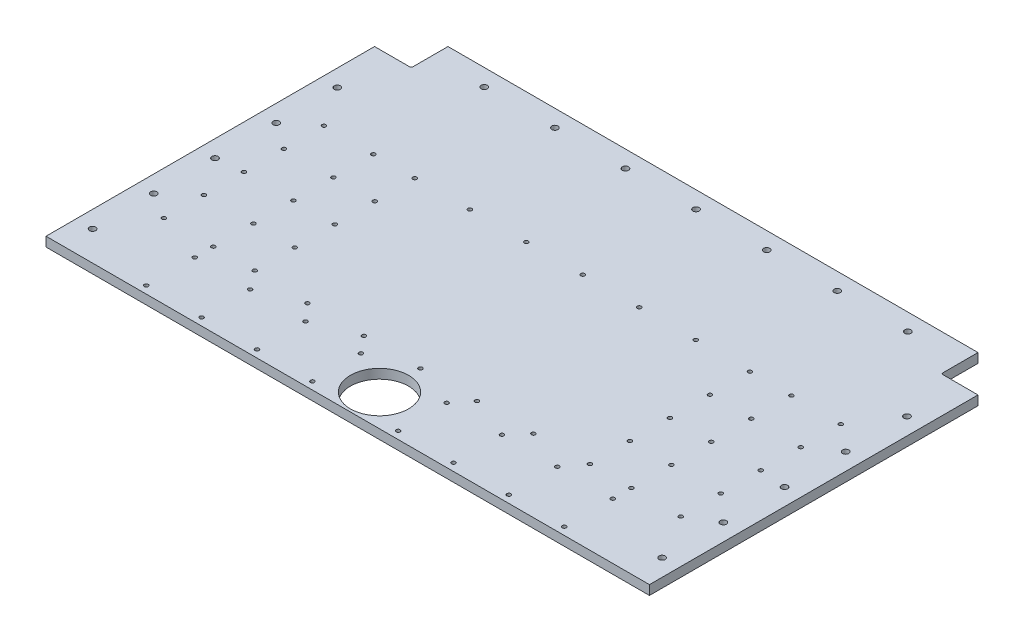
SolidWorks part; units mm, degrees
material "3.1355 (EN-AW 2024)"
ref_plane "Спереди" through (0, 0, 0) normal (0, 0, 1) x (1, 0, 0)
ref_plane "Сверху" through (0, 0, 0) normal (0, 1, 0) x (1, 0, 0)
ref_plane "Справа" through (0, 0, 0) normal (1, 0, 0) x (0, 0, -1)
sketch "Эскиз1" plane through (0, 0, 0) normal (0, 1, 0) x (1, 0, 0)
  line L1 (-320.5, 194) -> (320.5, 194)
  line L2 (-320.5, 194) -> (-320.5, -194)
  line L3 (-320.5, -194) -> (320.5, -194)
  line L4 (320.5, 194) -> (320.5, -194)
  line L5 (-320.5, 194) -> (320.5, -194) construction
  line L6 (-320.5, -194) -> (320.5, 194) construction
  point P0 (0, 0)
  dimension "D1" = 641
  dimension "D2" = 388
extrude "База" add sketch "Эскиз1" along normal blind 10
hole_wizard "Винты M6" positions "Эскиз2" profile "Эскиз3" countersink size "M6" standard "DIN" end condition through all
sketch "Эскиз2" plane through (0, 0, 0) normal (0, -1, 0) x (-1, 0, 0)
  line L2 (-302.5, -97.5) -> (-302.5, -32.5) construction
  line L3 (-302.5, -32.5) -> (-302.5, 32.5) construction
  line L4 (-302.5, 32.5) -> (-302.5, 97.5) construction
  line L7 (-320.5, -194) -> (-320.5, 194) construction
  line L8 (0, 176) -> (-75, 176) construction
  line L9 (-75, 176) -> (-150, 176) construction
  line L10 (-150, 176) -> (-225, 176) construction
  line L15 (-320.5, 194) -> (320.5, 194) construction
  line L16 (-302.5, -162.5) -> (-302.5, -97.5) construction
  point P4 (-302.5, -97.5)
  point P6 (-302.5, -32.5)
  point P8 (-302.5, 32.5)
  point P12 (-302.5, 97.5)
  point P36 (0, 176)
  point P38 (-75, 176)
  point P40 (-150, 176)
  point P42 (-225, 176)
  point P67 (-302.5, 0)
  point P68 (-302.5, -162.5)
  dimension "D1" = 65
  dimension "D2" = 18
  dimension "D3" = 18
  dimension "D4" = 75
sketch "Эскиз3" plane through (302.5, 0, 97.5) normal (1, 0, 0) x (0, 0, -1)
  line L0 (0, 0) -> (0, 10)
  line L1 (0, 10) -> (3.3, 10)
  line L2 (3.3, 10) -> (3.3, 3)
  line L3 (3.3, 3) -> (6.3, 0)
  line L5 (6.3, 0) -> (0, 0)
  line L6 (-3.3, 3) -> (-6.3, 0) construction
  line L11 (0, -6.35) -> (0, 107.95) construction
  dimension "Диаметр сквозного отверстия" = 6.6
  dimension "Глубина сквозного отверстия" = 10
  dimension "Диаметр передней зенковки" = 12.6
  dimension "Угол передней зенковки" = 90
mirror "Зеркальное отражение1" about plane through (0, 0, 0) normal (1, 0, 0) of "Винты M6"
sketch "Эскиз4" plane through (0, 0, 0) normal (0, -1, 0) x (1, 0, 0)
  line L1 (-320.5, -194) -> (-281.5, -194)
  line L2 (-320.5, -194) -> (-320.5, -155)
  line L3 (-320.5, -155) -> (-281.5, -155)
  line L4 (-281.5, -194) -> (-281.5, -155)
  line L5 (320.5, -194) -> (281.5, -194)
  line L6 (320.5, -194) -> (320.5, -155)
  line L7 (320.5, -155) -> (281.5, -155)
  line L8 (281.5, -194) -> (281.5, -155)
  dimension "D1" = 39
extrude "ВырезПрофиля" cut sketch "Эскиз4" against normal through all
fillet "Скругление1" radius 1.5 2 edges at (281.5, 5, -155) (-281.5, 5, -155)
sketch "РазмерСтола" plane through (0, 10, 0) normal (0, 1, 0) x (1, 0, 0)
  line L0 (281.5, 194) -> (-281.5, 194) construction
  line L1 (-130, 49.7) -> (130, 49.7) construction
  line L2 (-130, 49.7) -> (-130, -100.3) construction
  line L3 (-130, -100.3) -> (130, -100.3) construction
  line L4 (130, 49.7) -> (130, -100.3) construction
  point P6 (0, 49.7)
  dimension "D1" = 144.3
  dimension "D2" = 260
  dimension "D3" = 150
sketch "ДополнительныеЗоны" plane through (0, 10, 0) normal (0, 1, 0) x (1, 0, 0)
  line L0 (-320.5, -194) -> (320.5, -194) construction
  line L3 (-170, 66.5) -> (170, 66.5) construction
  line L5 (-170, 66.5) -> (-230, 66.5) construction
  line L7 (-170, -126.5) -> (-230, -126.5) construction
  line L8 (-230, 66.5) -> (-230, -126.5) construction
  line L9 (170, 66.5) -> (230, 66.5) construction
  line L11 (170, -126.5) -> (230, -126.5) construction
  line L12 (230, 66.5) -> (230, -126.5) construction
  line L13 (-230, -126.5) -> (-37.5, -126.5) construction
  line L14 (-230, -126.5) -> (-230, -194) construction
  line L15 (-230, -194) -> (-37.5, -194) construction
  line L16 (-37.5, -126.5) -> (-37.5, -194) construction
  line L18 (230, -126.5) -> (37.5, -126.5) construction
  line L19 (230, -126.5) -> (230, -194) construction
  line L20 (230, -194) -> (37.5, -194) construction
  line L21 (37.5, -126.5) -> (37.5, -194) construction
  line L23 (-170, 66.5) -> (-170, -126.5) construction
  line L24 (-170, -126.5) -> (170, -126.5) construction
  line L25 (170, 66.5) -> (170, -126.5) construction
  point P0 (0, 66.5)
  dimension "D1" = 60
  dimension "D2" = 75
  dimension "D3" = 67.5
  dimension "D4" = 193
  dimension "D5" = 460
hole_wizard "M5" positions "Эскиз6" profile "Эскиз7" tap size "M5" standard "DIN" end condition through all
sketch "Эскиз6" plane through (0, 0, 0) normal (0, -1, 0) x (-1, 0, 0)
  line L12 (130, -100.3) -> (-130, -100.3) construction
  line L13 (130, 49.7) -> (-130, 49.7) construction
  line L14 (120, 55.7) -> (60, 55.7) construction
  line L15 (60, 55.7) -> (0, 55.7) construction
  line L16 (0, 55.7) -> (-60, 55.7) construction
  line L17 (-60, 55.7) -> (-120, 55.7) construction
  line L18 (274.5, -114.75) -> (274.5, -72.25) construction
  line L19 (274.5, -72.25) -> (274.5, -29.75) construction
  line L20 (274.5, -29.75) -> (274.5, 12.75) construction
  line L21 (274.5, 12.75) -> (274.5, 55.25) construction
  line L22 (222, 55.25) -> (230, 55.25) construction
  line L23 (230, 66.5) -> (230, -126.5) construction
  line L26 (178, 55.25) -> (170, 55.25) construction
  line L30 (-178, 55.25) -> (-170, 55.25) construction
  line L34 (-222, 55.25) -> (-230, 55.25) construction
  line L35 (-230, 66.5) -> (-230, -126.5) construction
  line L39 (222, -186) -> (163.1667, -186) construction
  line L40 (163.1667, -186) -> (104.3333, -186) construction
  line L41 (104.3333, -186) -> (45.5, -186) construction
  line L44 (222, -186) -> (230, -186) construction
  line L45 (230, -126.5) -> (230, -194) construction
  line L48 (222, -186) -> (222, -194) construction
  line L49 (230, -194) -> (37.5, -194) construction
  line L52 (45.5, -186) -> (37.5, -186) construction
  line L53 (37.5, -126.5) -> (37.5, -194) construction
  line L56 (222, -134.5) -> (222, -126.5) construction
  line L57 (170, -126.5) -> (230, -126.5) construction
  line L61 (-222, -186) -> (-230, -186) construction
  line L62 (-230, -126.5) -> (-230, -194) construction
  line L65 (-222, -186) -> (-222, -194) construction
  line L66 (-230, -194) -> (-37.5, -194) construction
  line L69 (-222, -186) -> (-163.1667, -186) construction
  line L70 (-163.1667, -186) -> (-104.3333, -186) construction
  line L71 (-104.3333, -186) -> (-45.5, -186) construction
  line L72 (-45.5, -186) -> (-37.5, -186) construction
  line L73 (-37.5, -126.5) -> (-37.5, -194) construction
  line L76 (-222, -134.5) -> (-222, -126.5) construction
  line L77 (-170, -126.5) -> (-230, -126.5) construction
  line L95 (170, 66.5) -> (170, -126.5) construction
  line L96 (-170, 66.5) -> (-170, -126.5) construction
  point P0 (0, 55.7)
  point P2 (-60, 55.7)
  point P6 (-120, 55.7)
  point P8 (60, 55.7)
  point P12 (120, 55.7)
  point P34 (120, -116.8)
  point P38 (60, -116.8)
  point P40 (0, -116.8)
  point P42 (-60, -116.8)
  point P46 (-120, -116.8)
  point P57 (274.5, -114.75)
  point P60 (274.5, -29.75)
  point P63 (274.5, 55.25)
  point P82 (274.5, 12.75)
  point P84 (274.5, -72.25)
  point P99 (-274.5, 55.25)
  point P101 (-274.5, 12.75)
  point P103 (-274.5, -29.75)
  point P105 (-274.5, -72.25)
  point P107 (-274.5, -114.75)
  point P109 (222, 55.25)
  point P111 (178, 55.25)
  point P113 (222, 12.75)
  point P115 (178, 12.75)
  point P117 (222, -29.75)
  point P119 (178, -29.75)
  point P121 (222, -72.25)
  point P123 (178, -72.25)
  point P125 (178, -114.75)
  point P127 (222, -114.75)
  point P145 (-222, 55.25)
  point P147 (-178, 55.25)
  point P149 (-178, 12.75)
  point P151 (-222, 12.75)
  point P153 (-222, -29.75)
  point P155 (-178, -29.75)
  point P157 (-178, -72.25)
  point P159 (-222, -72.25)
  point P161 (-222, -114.75)
  point P163 (-178, -114.75)
  point P180 (222, -134.5)
  point P182 (222, -186)
  point P184 (163.1667, -134.5)
  point P186 (104.3333, -134.5)
  point P188 (45.5, -134.5)
  point P190 (45.5, -186)
  point P192 (104.3333, -186)
  point P194 (163.1667, -186)
  point P237 (-45.5, -134.5)
  point P239 (-104.3333, -134.5)
  point P241 (-163.1667, -134.5)
  point P243 (-222, -134.5)
  point P245 (-222, -186)
  point P247 (-163.1667, -186)
  point P249 (-104.3333, -186)
  point P251 (-45.5, -186)
  dimension "D1" = 240
  dimension "D2" = 6
  dimension "D3" = 16.5
  dimension "D4" = 29.75
  dimension "D5" = 274.5
  dimension "D6" = 170
  dimension "D7" = 274.5
  dimension "D8" = 8
  dimension "D9" = 8
sketch "Эскиз7" plane through (0, 0, -55.7) normal (1, 0, 0) x (0, 0, -1)
  line L0 (0, 0) -> (0, 10)
  line L1 (0, 10) -> (2.1, 10)
  line L2 (2.1, 10) -> (2.1, 0)
  line L5 (2.1, 0) -> (0, 0)
  line L11 (0, -6.35) -> (0, 107.95) construction
  dimension "Диаметр проходного сверла" = 4.2
  dimension "Глубина проходного сверла" = 10
cosmetic thread "Отверстие резьбы1" parameters "D2"=5
cosmetic thread "Отверстие резьбы3" parameters "D2"=5
cosmetic thread "Отверстие резьбы4" parameters "D2"=5
cosmetic thread "Отверстие резьбы5" parameters "D2"=5
cosmetic thread "Отверстие резьбы7" parameters "D2"=5
cosmetic thread "Отверстие резьбы8" parameters "D2"=5
cosmetic thread "Отверстие резьбы10" parameters "D2"=5
cosmetic thread "Отверстие резьбы11" parameters "D2"=5
cosmetic thread "Отверстие резьбы13" parameters "D2"=5
cosmetic thread "Отверстие резьбы14" parameters "D2"=5
cosmetic thread "Отверстие резьбы15" parameters "D2"=5
cosmetic thread "Отверстие резьбы16" parameters "D2"=5
cosmetic thread "Отверстие резьбы17" parameters "D2"=5
cosmetic thread "Отверстие резьбы18" parameters "D2"=5
cosmetic thread "Отверстие резьбы19" parameters "D2"=5
cosmetic thread "Отверстие резьбы20" parameters "D2"=5
cosmetic thread "Отверстие резьбы21" parameters "D2"=5
cosmetic thread "Отверстие резьбы22" parameters "D2"=5
cosmetic thread "Отверстие резьбы23" parameters "D2"=5
cosmetic thread "Отверстие резьбы24" parameters "D2"=5
cosmetic thread "Отверстие резьбы32" parameters "D2"=5
cosmetic thread "Отверстие резьбы33" parameters "D2"=5
cosmetic thread "Отверстие резьбы34" parameters "D2"=5
cosmetic thread "Отверстие резьбы35" parameters "D2"=5
cosmetic thread "Отверстие резьбы36" parameters "D2"=5
cosmetic thread "Отверстие резьбы37" parameters "D2"=5
cosmetic thread "Отверстие резьбы38" parameters "D2"=5
cosmetic thread "Отверстие резьбы39" parameters "D2"=5
cosmetic thread "Отверстие резьбы40" parameters "D2"=5
cosmetic thread "Отверстие резьбы41" parameters "D2"=5
cosmetic thread "Отверстие резьбы42" parameters "D2"=5
cosmetic thread "Отверстие резьбы43" parameters "D2"=5
cosmetic thread "Отверстие резьбы44" parameters "D2"=5
cosmetic thread "Отверстие резьбы45" parameters "D2"=5
cosmetic thread "Отверстие резьбы46" parameters "D2"=5
cosmetic thread "Отверстие резьбы47" parameters "D2"=5
cosmetic thread "Отверстие резьбы48" parameters "D2"=5
cosmetic thread "Отверстие резьбы49" parameters "D2"=5
cosmetic thread "Отверстие резьбы50" parameters "D2"=5
cosmetic thread "Отверстие резьбы51" parameters "D2"=5
cosmetic thread "Отверстие резьбы52" parameters "D2"=5
cosmetic thread "Отверстие резьбы53" parameters "D2"=5
cosmetic thread "Отверстие резьбы54" parameters "D2"=5
cosmetic thread "Отверстие резьбы55" parameters "D2"=5
cosmetic thread "Отверстие резьбы56" parameters "D2"=5
cosmetic thread "Отверстие резьбы57" parameters "D2"=5
cosmetic thread "Отверстие резьбы58" parameters "D2"=5
cosmetic thread "Отверстие резьбы59" parameters "D2"=5
cosmetic thread "Отверстие резьбы60" parameters "D2"=5
cosmetic thread "Отверстие резьбы61" parameters "D2"=5
cosmetic thread "Отверстие резьбы62" parameters "D2"=5
cosmetic thread "Отверстие резьбы63" parameters "D2"=5
cosmetic thread "Отверстие резьбы64" parameters "D2"=5
cosmetic thread "Отверстие резьбы65" parameters "D2"=5
cosmetic thread "Отверстие резьбы66" parameters "D2"=5
cosmetic thread "Отверстие резьбы67" parameters "D2"=5
sketch "Эскиз8" plane through (0, 10, 0) normal (0, 1, 0) x (1, 0, 0)
  line L0 (-320.5, -194) -> (320.5, -194) construction
  line L1 (-37.5, -126.5) -> (-37.5, -194) construction
  circle A0 centre (0, -160.25) radius 30.9
  point P6 (-37.5, -160.25)
  point P7 (0, -194)
  dimension "D1" = 61.8
extrude "Камера" cut sketch "Эскиз8" against normal through all
